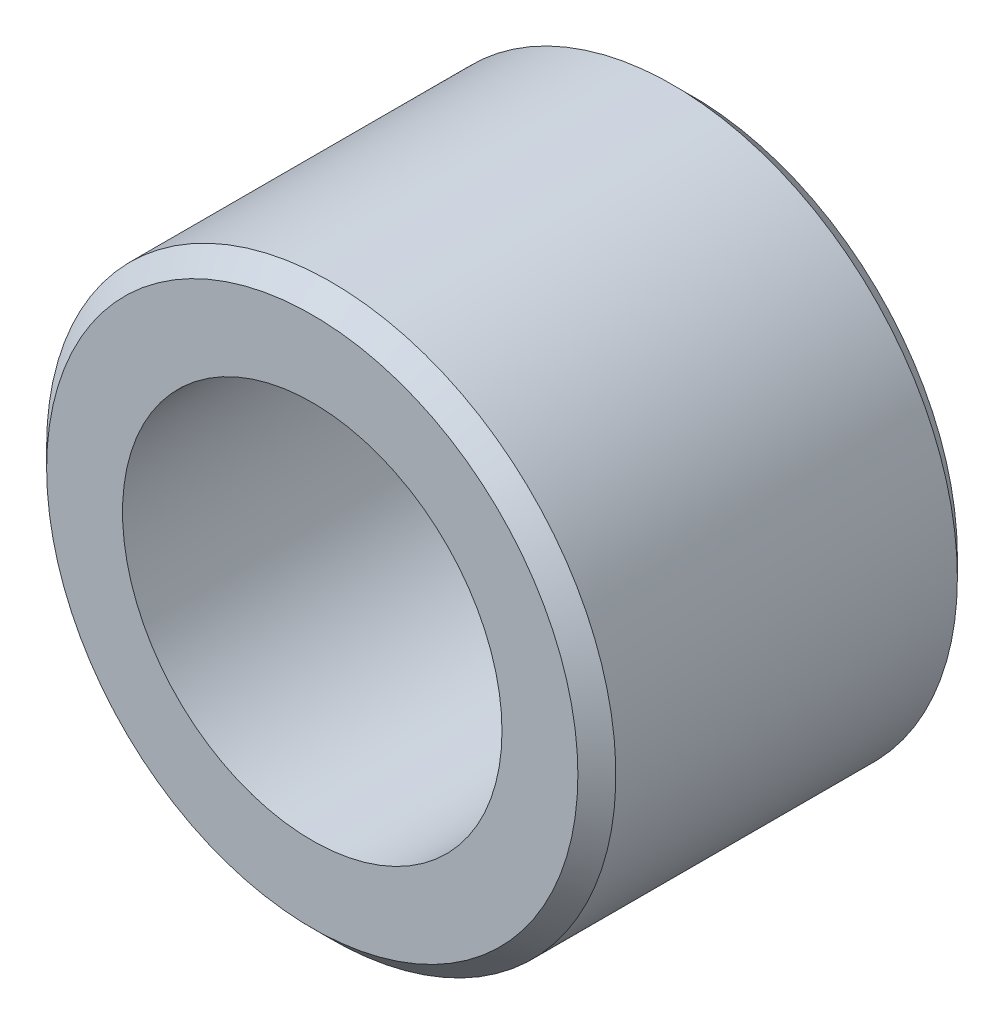
SolidWorks part; units mm, degrees
material "Plain Carbon Steel"
ref_plane "Front Plane" through (0, 0, 0) normal (0, 0, 1) x (1, 0, 0)
ref_plane "Top Plane" through (0, 0, 0) normal (0, 1, 0) x (1, 0, 0)
ref_plane "Right Plane" through (0, 0, 0) normal (1, 0, 0) x (0, 0, -1)
sketch "Sketch1" plane through (0, 0, 0) normal (0, 0, 1) x (1, 0, 0)
  circle A0 centre (0, 0) radius 1
  circle A1 centre (0, 0) radius 1.5
  dimension "D1" = 3
  dimension "D2" = 2
extrude "Boss-Extrude1" add sketch "Sketch1" along normal blind 2
chamfer "Chamfer1" distance 0.1 angle 45 2 edges at (1.5, 0, 0) (1.5, 0, 2)
